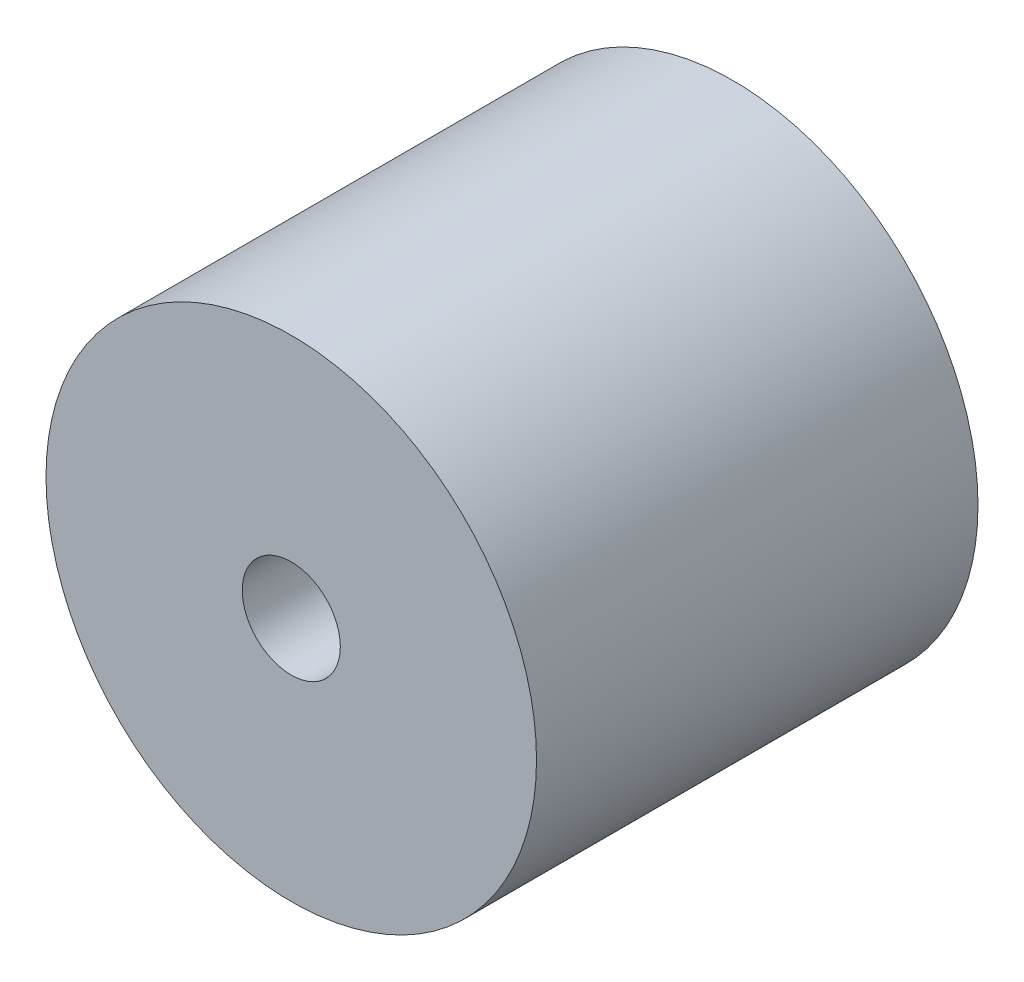
SolidWorks part; units mm, degrees
ref_plane "Front Plane" through (0, 0, 0) normal (0, 0, 1) x (1, 0, 0)
ref_plane "Top Plane" through (0, 0, 0) normal (0, 1, 0) x (1, 0, 0)
ref_plane "Right Plane" through (0, 0, 0) normal (1, 0, 0) x (0, 0, -1)
sketch "Sketch1" plane through (0, 0, 0) normal (0, 0, 1) x (1, 0, 0)
  circle A0 centre (0, 0) radius 15
  circle A6 centre (0, 0) radius 3
  dimension "D1" = 30
  dimension "D2" = 6
extrude "Boss-Extrude1" add sketch "Sketch1" along normal blind 27
